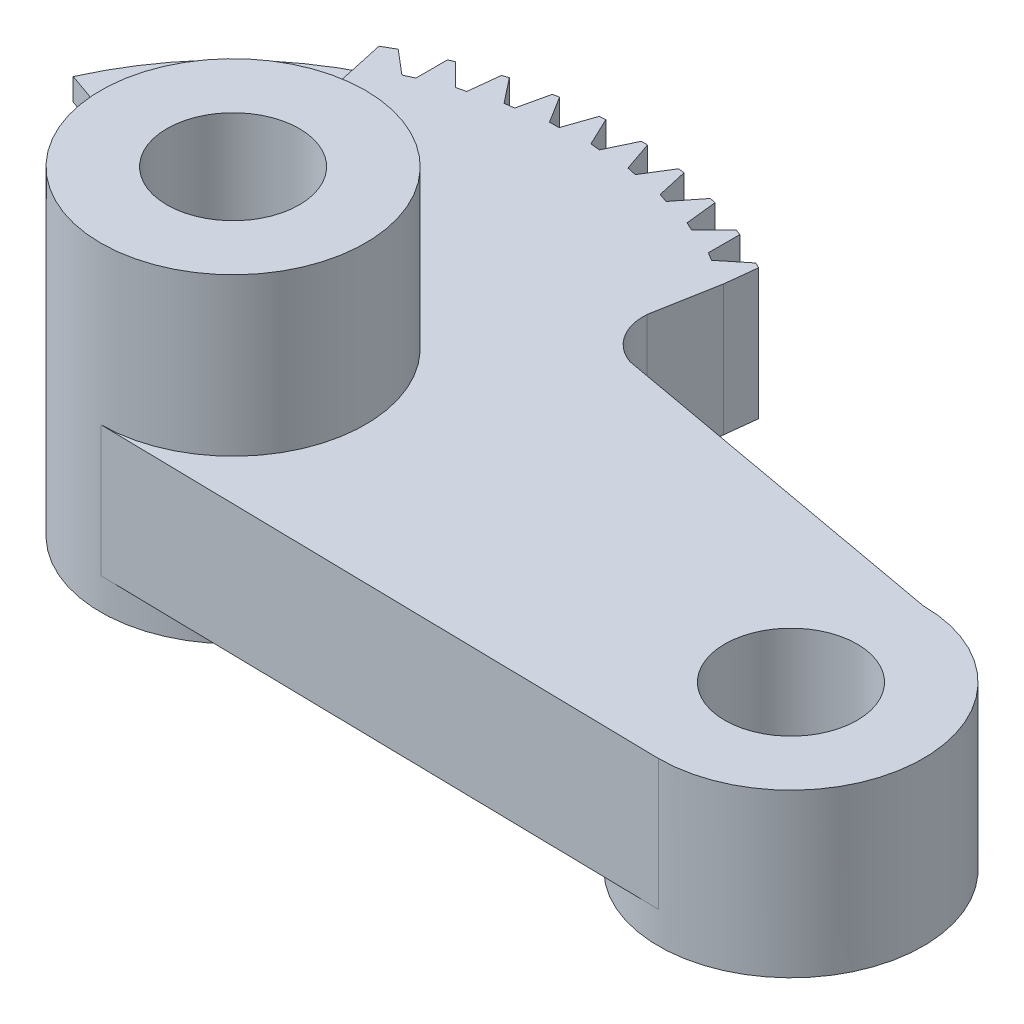
SolidWorks part; units mm, degrees
ref_plane "Спереди" through (0, 0, 0) normal (0, 0, 1) x (1, 0, 0)
ref_plane "Сверху" through (0, 0, 0) normal (0, 1, 0) x (1, 0, 0)
ref_plane "Справа" through (0, 0, 0) normal (1, 0, 0) x (0, 0, -1)
sketch "Эскиз1" plane through (0, 0, 0) normal (0, 1, 0) x (1, 0, 0)
  line L0 (-8.1147, 3.9642) -> (30.3411, -3.1046) construction
  line L1 (-7.0258, 12.1759) -> (-7.131, 12.6394)
  line L2 (0, -5) -> (21.4669, -5.3883)
  line L3 (21.4669, 4.6117) -> (7.9243, 7.0621)
  line L4 (6.718, 8.9283) -> (7.1612, 11.3779)
  line L5 (-2.8983, 13.1359) -> (-3.6342, 14.0716)
  line L6 (-4.339, 12.734) -> (-5.1742, 13.5822)
  line L7 (-3.9893, 12.8157) -> (-3.8571, 13.9987)
  line L9 (-7.131, 12.6394) -> (-6.6667, 12.9059)
  line L10 (-6.6667, 12.9059) -> (-5.7516, 12.1288)
  line L11 (-5.7516, 12.1288) -> (-5.3876, 12.2946)
  line L12 (-3.8571, 13.9987) -> (-3.6342, 14.0716)
  line L13 (-1.422, 13.3754) -> (-2.0494, 14.387)
  line L14 (-2.5417, 13.1782) -> (-2.279, 14.3393)
  line L39 (-2.279, 14.3393) -> (-2.0494, 14.387)
  line L40 (0.0718, 13.4494) -> (-0.4394, 14.5244)
  line L41 (-1.0629, 13.3778) -> (-0.6729, 14.5025)
  line L42 (-0.6729, 14.5025) -> (-0.4394, 14.5244)
  line L43 (1.5646, 13.3571) -> (1.1759, 14.4822)
  line L44 (0.4289, 13.412) -> (0.9414, 14.4864)
  line L45 (0.9414, 14.4864) -> (1.1759, 14.4822)
  line L46 (3.0379, 13.0996) -> (2.7766, 14.261)
  line L47 (1.9154, 13.2803) -> (2.544, 14.2911)
  line L48 (2.544, 14.2911) -> (2.7766, 14.261)
  line L49 (4.4735, 12.6801) -> (4.3427, 13.8633)
  line L50 (3.378, 12.9843) -> (4.1149, 13.9191)
  line L51 (4.1149, 13.9191) -> (4.3427, 13.8633)
  line L52 (5.8536, 12.1038) -> (5.8551, 13.2942)
  line L53 (4.7987, 12.5278) -> (5.6349, 13.375)
  line L54 (5.6349, 13.375) -> (5.8551, 13.2942)
  line L55 (7.1612, 11.3779) -> (7.2948, 12.5607)
  line L56 (6.1599, 11.9163) -> (7.085, 12.6654)
  line L57 (7.085, 12.6654) -> (7.2948, 12.5607)
  line L58 (-4.339, 12.734) -> (-3.9893, 12.8157)
  line L59 (-2.8983, 13.1359) -> (-2.5417, 13.1782)
  line L60 (-1.422, 13.3754) -> (-1.0629, 13.3778)
  line L61 (0.0718, 13.4494) -> (0.4289, 13.412)
  line L62 (1.5646, 13.3571) -> (1.9154, 13.2803)
  line L63 (3.0379, 13.0996) -> (3.378, 12.9843)
  line L64 (4.4735, 12.6801) -> (4.7987, 12.5278)
  line L65 (5.8536, 12.1038) -> (6.1599, 11.9163)
  line L66 (-5.3876, 13.485) -> (-5.3876, 12.2946)
  line L67 (-5.3876, 13.485) -> (-5.1742, 13.5822)
  line L68 (-5.2411, 3.925) -> (-4.7377, 1.5981)
  line L69 (-12.5111, 6.4702) -> (-5.2411, 3.925)
  arc A0 (-4.7377, 1.5981) -> (0, -5) centre (0, 0) ccw
  arc A1 (21.2861, -5.385) -> (21.4669, 4.6117) centre (21.4669, -0.3883) ccw
  arc A2 (7.9243, 7.0621) -> (6.718, 8.9283) centre (8.5382, 8.7819) cw
  arc A3 (-5.4397, 3.9952) -> (-5.4396, 3.9945) centre (1.2447, 4.6512) ccw
  arc A4 (-12.5111, 6.4702) -> (-7.0258, 12.1759) centre (-1.8095, 1.6715) cw
  circle A5 centre (21.4669, -0.3883) radius 2.5
  circle A6 centre (0, 0) radius 2.5
  point P23 (0, 0)
  point P89 (-0.0104, 0.0012)
  dimension "D2" = 1.8261
  dimension "D3" = 9
  dimension "D1" = 39.1
extrude "Бобышка-Вытянуть1" add sketch "Эскиз1" along normal blind 4.94
sketch "Эскиз2" plane through (0, 4.94, 0) normal (0, 1, 0) x (1, 0, 0)
  circle A0 centre (0, 0) radius 5
  circle A1 centre (0, 0) radius 2.5
extrude "Бобышка-Вытянуть2" add sketch "Эскиз2" along normal blind 5.94
sketch "Эскиз4" plane through (0, 0, 0) normal (0, -1, 0) x (1, 0, 0)
  line L0 (-5.2411, -3.925) -> (-7.0258, -12.1759)
  line L1 (-12.5111, -6.4702) -> (-5.2411, -3.925)
  arc A0 (-7.0258, -12.1759) -> (-12.5111, -6.4702) centre (-1.8095, -1.6715) cw
  dimension "D1" = 11.7282
extrude "Вырез-Вытянуть1" cut sketch "Эскиз4" against normal blind 3.5
sketch "Эскиз5" plane through (0, 4.94, 0) normal (0, 1, 0) x (1, 0, 0)
  line L0 (-5.2411, 3.925) -> (-7.0258, 12.1759)
  line L1 (-12.5111, 6.4702) -> (-5.2411, 3.925)
  arc A0 (-7.0258, 12.1759) -> (-12.5111, 6.4702) centre (-1.8095, 1.6715) ccw
  dimension "D1" = 11.7282
extrude "Вырез-Вытянуть3" cut sketch "Эскиз5" against normal blind 0.6
sketch "Эскиз6" plane through (0, 0, 0) normal (0, -1, 0) x (1, 0, 0)
  circle A0 centre (0, 0) radius 5
  circle A1 centre (0, 0) radius 2.5
  circle A2 centre (21.4669, 0.3883) radius 2.5
  circle A3 centre (21.4669, 0.3883) radius 5
extrude "Бобышка-Вытянуть4" add sketch "Эскиз6" along normal blind 1.2
